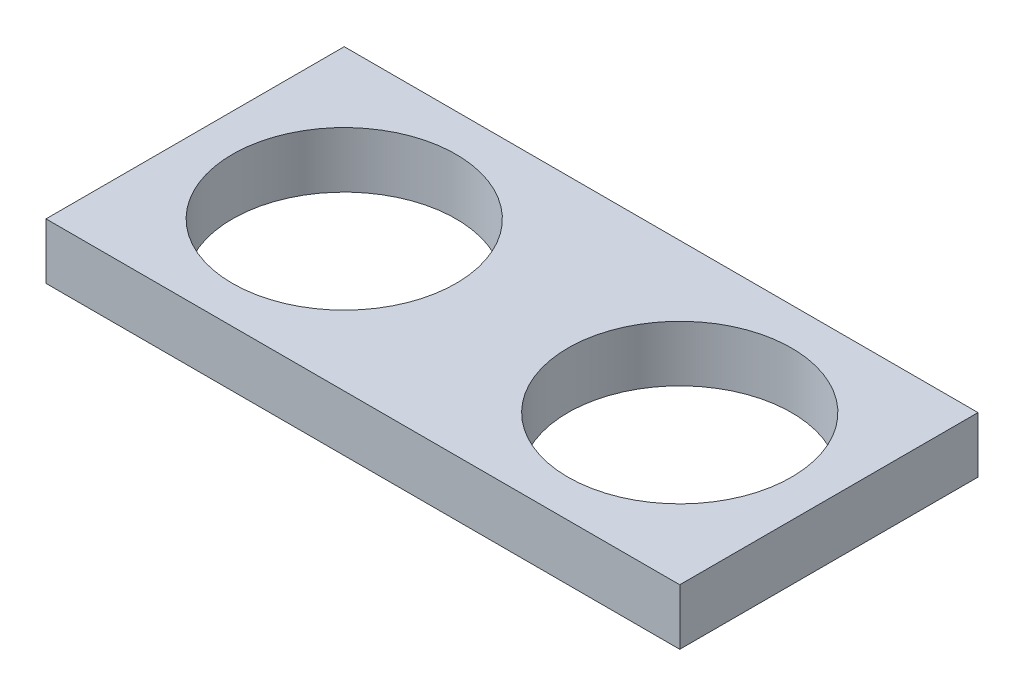
SolidWorks part; units mm, degrees
ref_plane "Front Plane" through (0, 0, 0) normal (0, 0, 1) x (1, 0, 0)
ref_plane "Top Plane" through (0, 0, 0) normal (0, 1, 0) x (1, 0, 0)
ref_plane "Right Plane" through (0, 0, 0) normal (1, 0, 0) x (0, 0, -1)
sketch "Sketch1" plane through (0, 0, 0) normal (0, 1, 0) x (1, 0, 0)
  line L0 (8, 8) -> (26, 8) construction
  line L1 (0, 0) -> (34, 0)
  line L2 (0, 0) -> (0, 16)
  line L3 (0, 16) -> (34, 16)
  line L4 (34, 0) -> (34, 16)
  line L5 (0, 0) -> (34, 16) construction
  line L6 (0, 16) -> (34, 0) construction
  circle A0 centre (8, 8) radius 6
  circle A1 centre (26, 8) radius 6
  point P4 (17, 8)
  point P8 (17, 8)
  point P10 (6.3864, 8)
  point P12 (34, 15.8587)
  point P14 (0.0544, 15.9744)
  point P15 (34, 0.1575)
  point P16 (33.8864, 15.9465)
  point P17 (0.1265, 15.9404)
  point P18 (33.8612, 0)
  point P19 (0.1546, 0)
  point P20 (0, 0.1575)
  dimension "D2" = 12
  dimension "D3" = 34
  dimension "D1" = 16
  dimension "D4" = 18
extrude "Boss-Extrude1" add sketch "Sketch1" along normal blind 3
